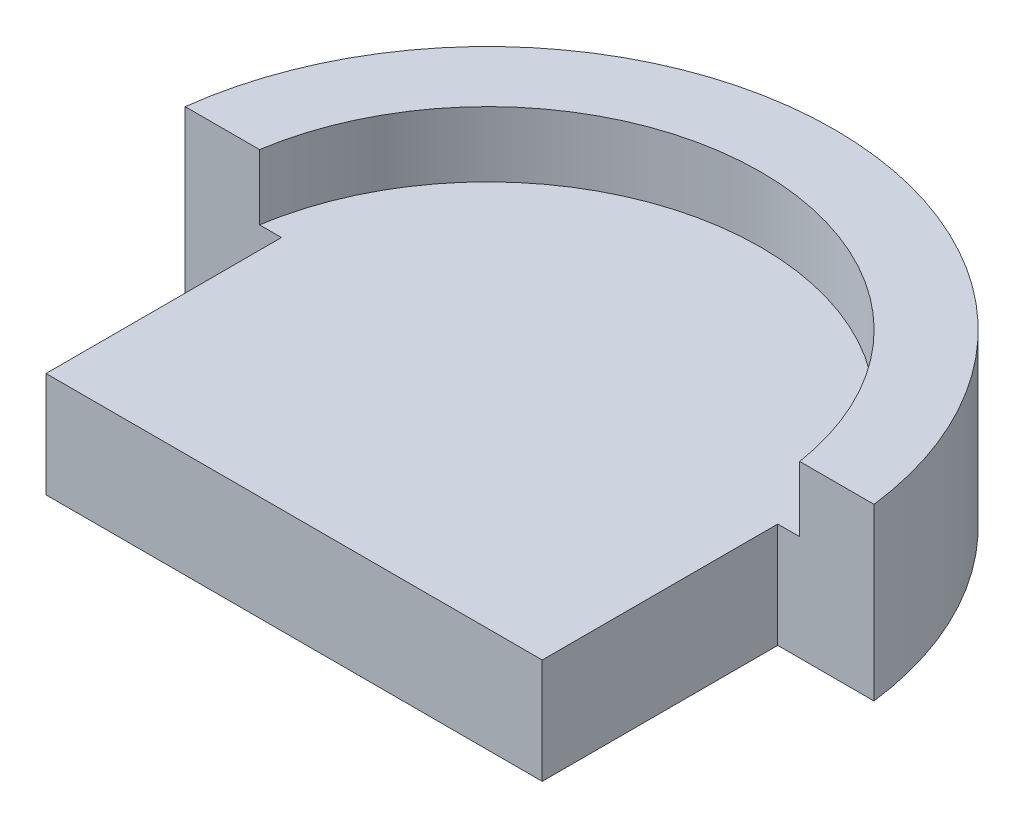
SolidWorks part; units mm, degrees
ref_plane "前视基准面" through (0, 0, 0) normal (0, 0, 1) x (1, 0, 0)
ref_plane "上视基准面" through (0, 0, 0) normal (0, 1, 0) x (1, 0, 0)
ref_plane "右视基准面" through (0, 0, 0) normal (1, 0, 0) x (0, 0, -1)
other "Configuration Table"
sketch "草图1" plane through (0, 0, 0) normal (0, 1, 0) x (1, 0, 0)
  line L0 (0, 4.6) -> (0, 0) construction
  line L1 (-5.9, 0) -> (5.9, 0)
  line L2 (-5.9, 0) -> (-5.9, 5.6)
  line L4 (5.9, 0) -> (5.9, 5.6)
  line L5 (-8.1892, 5.6) -> (-5.9, 5.6)
  line L6 (5.9, 5.6) -> (8.1892, 5.6)
  arc A0 (8.1892, 5.6) -> (-8.1892, 5.6) centre (0, 4.6) ccw
  point P5 (0, 0)
  dimension "D3" = 1
  dimension "D4" = 16.5
  dimension "D1" = 11.8
  dimension "D2" = 5.6
extrude "凸台-拉伸1" add sketch "草图1" along normal blind 2.5
sketch "草图2" plane through (0, 2.5, 0) normal (0, 1, 0) x (1, 0, 0)
  line L0 (-8.1892, 5.6) -> (-6.4226, 5.6)
  line L1 (-8.1892, 5.6) -> (-5.9, 5.6) construction
  line L2 (6.4226, 5.6) -> (8.1892, 5.6)
  line L3 (5.9, 5.6) -> (8.1892, 5.6) construction
  arc A0 (8.1892, 5.6) -> (-8.1892, 5.6) centre (0, 4.6) ccw construction
  arc A1 (8.1892, 5.6) -> (-8.1892, 5.6) centre (0, 4.6) ccw
  arc A2 (6.4226, 5.6) -> (-6.4226, 5.6) centre (0, 4.6) ccw
  dimension "D1" = 13
extrude "凸台-拉伸2" add sketch "草图2" along normal blind 1.55
sketch "草图3" plane through (0, 0, 0) normal (0, -1, 0) x (1, 0, 0)
  line L0 (0, 0) -> (0, -12.85) construction
  line L1 (-5.9, 0) -> (5.9, 0) construction
  circle A0 centre (-2.5, -4.1) radius 0.5
  circle A1 centre (2.5, -4.1) radius 0.5
  arc A2 (-8.1892, -5.6) -> (8.1892, -5.6) centre (0, -4.6) ccw construction
  dimension "D1" = 1
  dimension "D2" = 5
  dimension "D3" = 4.1
extrude "凸台-拉伸3" add sketch "草图3" along normal blind 0.5
